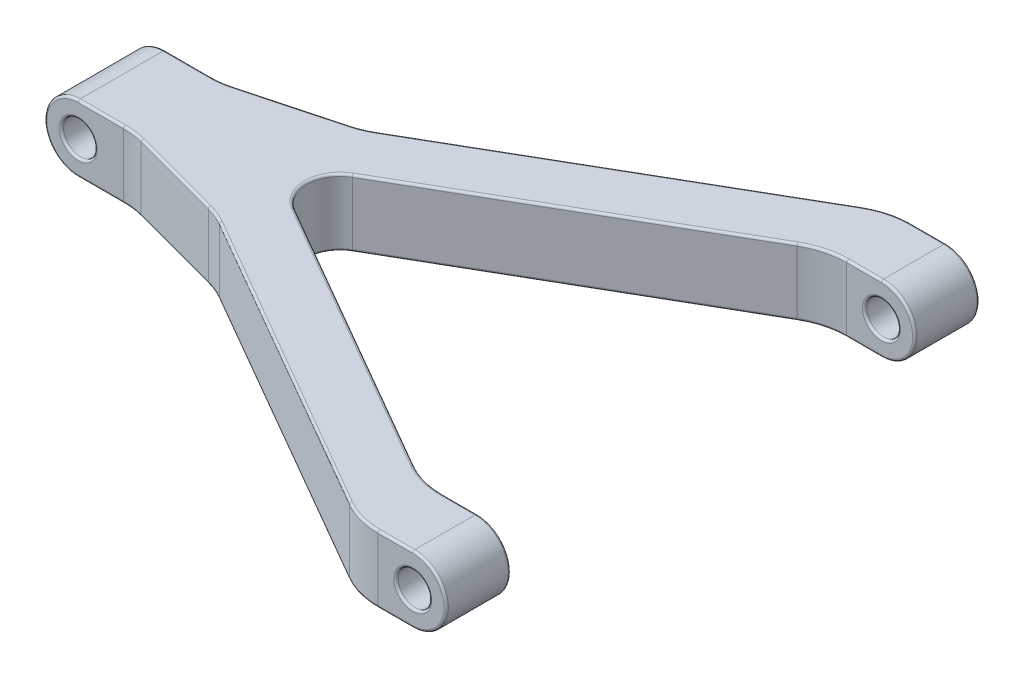
SolidWorks part; units mm, degrees
ref_plane "Alzado" through (0, 0, 0) normal (0, 0, 1) x (1, 0, 0)
ref_plane "Planta" through (0, 0, 0) normal (0, 1, 0) x (1, 0, 0)
ref_plane "Vista lateral" through (0, 0, 0) normal (1, 0, 0) x (0, 0, -1)
sketch "Croquis1" plane through (0, 0, 0) normal (0, 1, 0) x (1, 0, 0)
  line L0 (0, 0) -> (159.219, 0) construction
  line L1 (-194.7399, -39) -> (-194.7399, 39)
  line L2 (-194.7399, 39) -> (-144.7399, 39)
  line L3 (-144.7399, 39) -> (-44.7399, 65.7949)
  line L4 (-44.7399, 65.7949) -> (255.2601, 239)
  line L5 (255.2601, 239) -> (305.2601, 239)
  line L6 (255.2601, -239) -> (305.2601, -239)
  line L7 (-44.7399, -65.7949) -> (255.2601, -239)
  line L8 (-144.7399, -39) -> (-44.7399, -65.7949)
  line L9 (-194.7399, -39) -> (-144.7399, -39)
  line L10 (305.2601, 239) -> (305.2601, 181.26)
  line L11 (305.2601, 181.26) -> (255.2515, 181.26)
  line L12 (255.2515, 181.26) -> (-13.7, 25.9808)
  line L13 (-13.7, -25.9808) -> (255.2515, -181.26)
  line L14 (255.2515, -181.26) -> (305.2601, -181.26)
  line L15 (305.2601, -181.26) -> (305.2601, -239)
  arc A0 (-13.7, 25.9808) -> (-13.7, -25.9808) centre (1.3, 0) ccw
  point P17 (-194.7399, 0)
  point P21 (0, 0)
  dimension "D10" = 30
  dimension "D1" = 39
  dimension "D2" = 500
  dimension "D3" = 50
  dimension "D4" = 100
  dimension "D5" = 300
  dimension "D6" = 165
  dimension "D7" = 165
  dimension "D8" = 57.74
  dimension "D9" = 50
  dimension "D11" = 1.3
extrude "Saliente-Extruir1" add sketch "Croquis1" along normal blind 60 contours L15 L6 L7 L8 L9 L1 L2 L3 L4 L5 L10 L11 L12 A0 L13 L14
sketch "Croquis2" plane through (0, 0, 39) normal (0, 0, 1) x (1, 0, 0)
  line L0 (-194.7399, 60) -> (-194.7399, 0) construction
  circle A0 centre (-194.7399, 30) radius 30
extrude "Saliente-Extruir2" add sketch "Croquis2" against normal up to surface (78 mm away) up to face at (-169.7399, 30, -39)
sketch "Croquis3" plane through (0, 0, 39) normal (0, 0, 1) x (1, 0, 0)
  circle A0 centre (-194.7399, 30) radius 15
  dimension "D1" = 30
extrude "Cortar-Extruir1" cut sketch "Croquis3" against normal up to next
sketch "Croquis4" plane through (0, 0, 239) normal (0, 0, 1) x (1, 0, 0)
  line L0 (305.2601, 60) -> (305.2601, 0) construction
  circle A0 centre (305.2601, 30) radius 30
extrude "Saliente-Extruir3" add sketch "Croquis4" against normal up to surface (57.74 mm away) up to face at (280.2558, 30, 181.26)
sketch "Croquis5" plane through (0, 0, -239) normal (0, 0, -1) x (-1, 0, 0)
  line L0 (-305.2601, 60) -> (-305.2601, 0) construction
  circle A0 centre (-305.2601, 30) radius 30
extrude "Saliente-Extruir4" add sketch "Croquis5" against normal up to surface (57.74 mm away) up to face at (280.2558, 30, -181.26)
sketch "Croquis6" plane through (0, 0, 239) normal (0, 0, 1) x (1, 0, 0)
  circle A0 centre (305.2601, 30) radius 15
  dimension "D1" = 30
extrude "Cortar-Extruir2" cut sketch "Croquis6" against normal through all both and the other way through all
fillet "Redondeo1" radius 70 8 edges at (-44.7399, 30, 65.7949) (-144.7399, 30, 39) (-144.7399, 30, -39) (-44.7399, 30, -65.7949) (255.2601, 30, -239) (255.2515, 30, -181.26) (255.2515, 30, 181.26) (255.2601, 30, 239)
fillet "Redondeo2" radius 2 54 edges at (335.2601, 30, -181.26) (335.2601, 30, -239) (289.6341, 0, -181.26) (255.8906, 0, -178.8748) (112.654, 0, -98.9313) (-28.7, 0, 0) (112.654, 0, 98.9313) (255.8906, 0, 178.8748) (289.6341, 0, 181.26) (335.2601, 30, 181.26) (335.2601, 30, 239) (-224.7399, 30, -39) (-224.7399, 30, 39) (-174.3477, 0, 39) (-144.8187, 0, 39.5989) (-94.7399, 0, 52.3975) (-44.971, 0, 66.353) (101.1289, 0, 150.0123) (255.8993, 0, 236.6148) (289.6384, 0, 239) (-174.3477, 0, -39) (-144.8187, 0, -39.5989) (-94.7399, 0, -52.3975) (-44.971, 0, -66.353) (101.1289, 0, -150.0123) (255.8993, 0, -236.6148) (289.6384, 0, -239) (289.6341, 60, -181.26) (255.8906, 60, -178.8748) (112.654, 60, -98.9313) (-28.7, 60, 0) (112.654, 60, 98.9313) (255.8906, 60, 178.8748) (289.6341, 60, 181.26) (289.6384, 60, 239) (255.8993, 60, 236.6148) (101.1289, 60, 150.0123) (-44.971, 60, 66.353) (-94.7399, 60, 52.3975) (-144.8187, 60, 39.5989) (-174.3477, 60, 39) (-174.3477, 60, -39) (-144.8187, 60, -39.5989) (-94.7399, 60, -52.3975) (-44.971, 60, -66.353) (101.1289, 60, -150.0123) (255.8993, 60, -236.6148) (289.6384, 60, -239) (290.2601, 30, 181.26) (320.2601, 30, -181.26) (320.2601, 30, -239) (290.2601, 30, 239) (-179.7399, 30, 39) (-209.7399, 30, -39)
